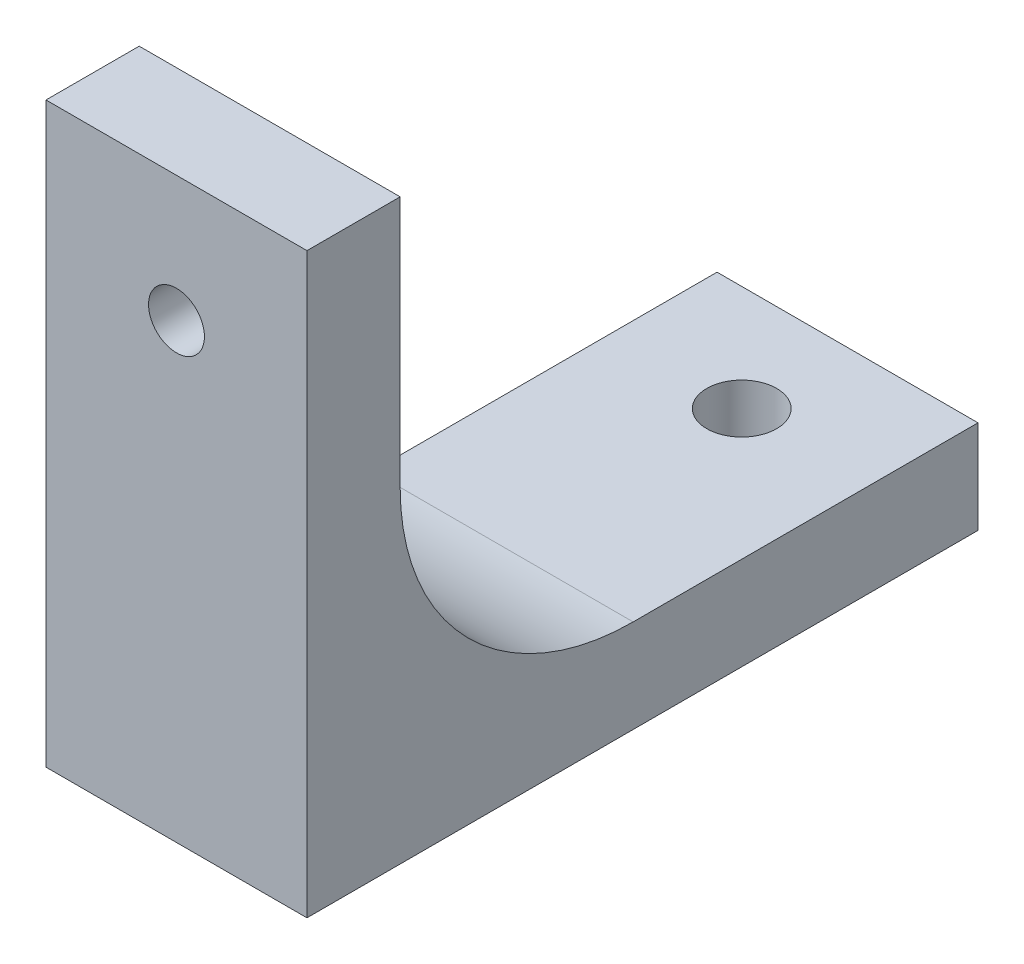
SolidWorks part; units mm, degrees
ref_plane "Front Plane" through (0, 0, 0) normal (0, 0, 1) x (1, 0, 0)
ref_plane "Top Plane" through (0, 0, 0) normal (0, 1, 0) x (1, 0, 0)
ref_plane "Right Plane" through (0, 0, 0) normal (1, 0, 0) x (0, 0, -1)
sketch "Sketch1" plane through (0, 0, 0) normal (1, 0, 0) x (0, 0, -1)
  line L0 (-17.231, 26.416) -> (-17.231, 12.7)
  line L1 (-17.231, -5.08) -> (14.265, -5.08)
  line L2 (-17.231, 26.416) -> (-22.311, 26.416)
  line L3 (-22.311, 26.416) -> (-22.311, -5.08)
  line L4 (-22.311, -5.08) -> (-17.231, -5.08)
  line L5 (14.265, -5.08) -> (14.265, 0)
  line L6 (14.265, 0) -> (-4.531, 0)
  arc A0 (-4.531, 0) -> (-17.231, 12.7) centre (-4.531, 12.7) cw
  dimension "D5" = 12.7
  dimension "D1" = 31.496
  dimension "D2" = 31.496
  dimension "D3" = 5.08
  dimension "D4" = 5.08
extrude "Boss-Extrude1" add sketch "Sketch1" along normal blind 14.224
sketch "Sketch2" plane through (0, 0, 22.311) normal (0, 0, 1) x (1, 0, 0)
  line L0 (7.112, 26.416) -> (7.112, -5.08) construction
  line L1 (14.224, 26.416) -> (0, 26.416) construction
  line L2 (14.224, -5.08) -> (0, -5.08) construction
  circle A0 centre (7.112, 19.558) radius 1.524
  dimension "D1" = 24.638
  dimension "D2" = 3.048
extrude "Cut-Extrude1" cut sketch "Sketch2" against normal through all
sketch "Sketch3" plane through (0, 0, 0) normal (0, 1, 0) x (1, 0, 0)
  line L0 (7.112, 14.265) -> (7.112, -4.531) construction
  line L1 (14.224, 14.265) -> (0, 14.265) construction
  line L2 (14.224, -4.531) -> (0, -4.531) construction
  circle A0 centre (7.112, 8.4981) radius 1.905
  dimension "D1" = 3.81
extrude "Cut-Extrude2" cut sketch "Sketch3" against normal through all contours A0
